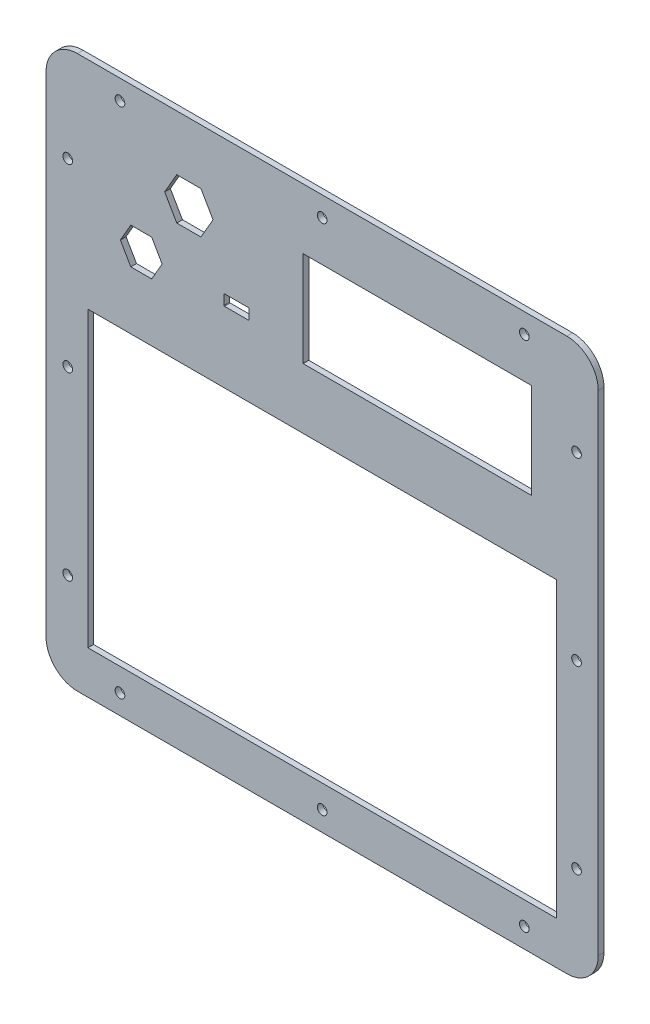
SolidWorks part; units mm, degrees
material "Alumina"
ref_plane "Front Plane" through (0, 0, 0) normal (0, 0, 1) x (1, 0, 0)
ref_plane "Top Plane" through (0, 0, 0) normal (0, 1, 0) x (1, 0, 0)
ref_plane "Right Plane" through (0, 0, 0) normal (1, 0, 0) x (0, 0, -1)
sketch "Sketch3" plane through (0, 0, 0) normal (0, 0, 1) x (1, 0, 0)
  line L0 (-123, 31.5) -> (123, 31.5)
  line L1 (-123, 31.5) -> (-123, -122.5)
  line L2 (-123, -122.5) -> (123, -122.5)
  line L3 (123, 31.5) -> (123, -122.5)
  line L8 (-38.77, 74.35) -> (-51.23, 74.35)
  line L9 (-51.54, 74.04) -> (-51.54, 68.96)
  line L10 (-51.23, 68.65) -> (-38.77, 68.65)
  line L11 (-38.46, 68.96) -> (-38.46, 74.04)
  line L12 (-10, 113.25) -> (110, 113.25)
  line L13 (-128.49, -145) -> (128.49, -145)
  line L14 (-145, -128.49) -> (-145, 128.49)
  line L15 (-128.49, 145) -> (128.49, 145)
  line L16 (145, -128.49) -> (145, 128.49)
  line L29 (-10, 113.25) -> (-10, 63.25)
  line L30 (-10, 63.25) -> (110, 63.25)
  line L31 (110, 113.25) -> (110, 63.25)
  line L32 (-70, 105) -> (-70, 71.5) construction
  line L33 (-57.2983, 105) -> (-63.6491, 116)
  line L34 (-84.0303, 71.5) -> (-89.5152, 81)
  line L35 (-89.5152, 81) -> (-100.4848, 81)
  line L36 (-100.4848, 81) -> (-105.9697, 71.5)
  line L37 (-105.9697, 71.5) -> (-100.4848, 62)
  line L38 (-100.4848, 62) -> (-89.5152, 62)
  line L39 (-89.5152, 62) -> (-84.0303, 71.5)
  line L40 (-63.6491, 116) -> (-76.3509, 116)
  line L41 (-76.3509, 116) -> (-82.7017, 105)
  line L42 (-82.7017, 105) -> (-76.3509, 94)
  line L43 (-76.3509, 94) -> (-63.6491, 94)
  line L44 (-63.6491, 94) -> (-57.2983, 105)
  arc A0 (-38.77, 68.65) -> (-38.46, 68.96) centre (-38.77, 68.96) ccw
  arc A1 (-51.54, 68.96) -> (-51.23, 68.65) centre (-51.23, 68.96) ccw
  arc A2 (-38.77, 74.35) -> (-38.46, 74.04) centre (-38.77, 74.04) cw
  arc A3 (-51.23, 74.35) -> (-51.54, 74.04) centre (-51.23, 74.04) ccw
  arc A4 (128.49, -145) -> (145, -128.49) centre (128.49, -128.49) ccw
  arc A5 (-128.49, -145) -> (-145, -128.49) centre (-128.49, -128.49) cw
  arc A6 (128.49, 145) -> (145, 128.49) centre (128.49, 128.49) cw
  arc A7 (-145, 128.49) -> (-128.49, 145) centre (-128.49, 128.49) cw
  circle A10 centre (-95, 71.5) radius 9.5 construction
  circle A11 centre (-70, 105) radius 11 construction
  point P18 (0, -122.5)
  point P23 (0, -145)
  point P26 (-51.54, 71.5)
  point P30 (-70, 88.25)
  point P32 (-45, 74.35)
  point P44 (-10, 88.25)
  point P58 (145, 0)
  point P59 (0, 145)
  dimension "D5" = 0.31
  dimension "D6" = 16.51
  dimension "D10" = 22
  dimension "D25" = 19
  dimension "D7" = 25
  dimension "D1" = 246
  dimension "D2" = 154
  dimension "D3" = 12.46
  dimension "D4" = 5.08
  dimension "D9" = 22.5
  dimension "D11" = 40
  dimension "D12" = 50
  dimension "D13" = 25
  dimension "D17" = 120
  dimension "D18" = 50
  dimension "D20" = 35
  dimension "D21" = 290
  dimension "D22" = 290
  dimension "D26" = 40
extrude "Boss-Extrude1" add sketch "Sketch3" against normal blind 3 contours L31 L12 L29 L30 | A7 L14 A5 L13 A4 L16 A6 L15 A3 L8 A2 L11 A0 L10 A1 L9 L44 L43 L42 L41 L40 L33 L39 L38 L37 L36 L35 L34 L0 L3 L2 L1 L12 L31 L30 L29
sketch "Sketch4" plane through (0, 0, 0) normal (0, 0, 1) x (1, 0, 0)
  line L4 (0, 100.6663) -> (0, -110.5882) construction
  line L5 (-84.5431, 0) -> (100.6663, 0) construction
  circle A2 centre (-133.604, 94.742) radius 2.54
  circle A3 centre (-106.172, 134.62) radius 2.54
  circle A4 centre (-133.604, -94.742) radius 2.54
  circle A5 centre (-133.604, 0) radius 2.54
  circle A6 centre (0, 134.62) radius 2.54
  circle A7 centre (0, -134.62) radius 2.54
  circle A8 centre (-106.172, -134.62) radius 2.54
  circle A9 centre (106.172, -134.62) radius 2.54
  circle A10 centre (133.604, 0) radius 2.54
  circle A11 centre (133.604, -94.742) radius 2.54
  circle A12 centre (106.172, 134.62) radius 2.54
  circle A13 centre (133.604, 94.742) radius 2.54
  dimension "D1" = 94.742
  dimension "D3" = 5.08
  dimension "D4" = 134.62
  dimension "D5" = 106.172
  dimension "D2" = 133.604
extrude "Cut-Extrude1" cut sketch "Sketch4" against normal blind 47.752
